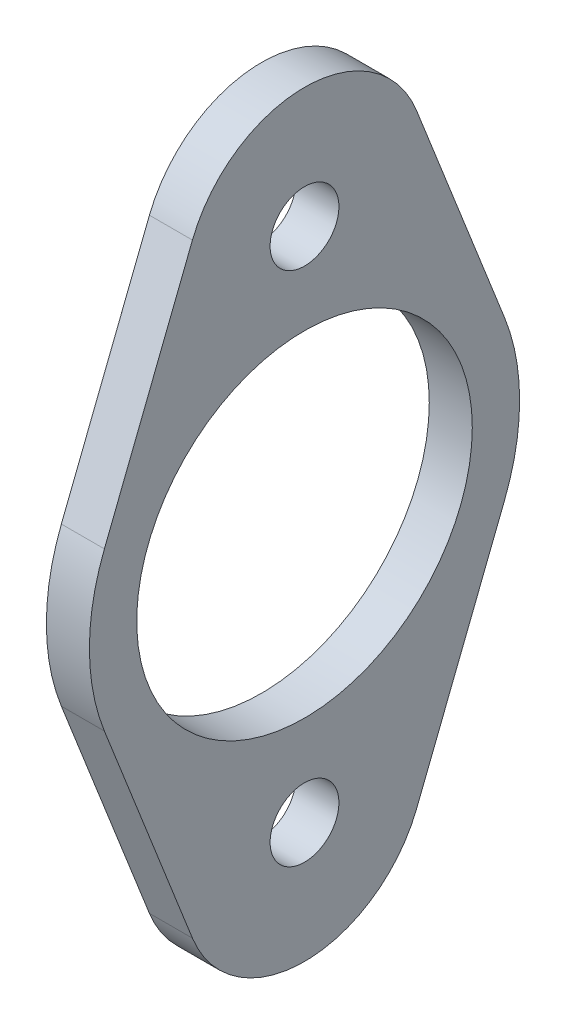
SolidWorks part; units mm, degrees
ref_plane "Front Plane" through (0, 0, 0) normal (1, 0, 0) x (0, 1, 0)
ref_plane "Top Plane" through (0, 0, 0) normal (0, 0, 1) x (0, 1, 0)
ref_plane "Right Plane" through (0, 0, 0) normal (0, 1, 0) x (-1, 0, 0)
sketch "Sketch1" plane through (0, 0, 0) normal (1, 0, 0) x (0, 1, 0)
  line L0 (-30, 0) -> (30, 0) construction
  line L1 (-35.1333, 13.0249) -> (-9.1667, 23.2588)
  line L2 (9.1667, 23.2588) -> (35.1333, 13.0249)
  line L3 (-35.1333, -13.0249) -> (-9.1667, -23.2588)
  line L4 (9.1667, -23.2588) -> (35.1333, -13.0249)
  circle A0 centre (0, 0) radius 19.5
  arc A1 (-9.1667, -23.2588) -> (9.1667, -23.2588) centre (0, 0) ccw
  circle A2 centre (30, 0) radius 4
  circle A3 centre (-30, 0) radius 4
  arc A4 (-35.1333, 13.0249) -> (-35.1333, -13.0249) centre (-30, 0) ccw
  circle A6 centre (-30, 0) radius 14 construction
  arc A7 (9.1667, 23.2588) -> (-9.1667, 23.2588) centre (0, 0) ccw
  arc A9 (35.1333, -13.0249) -> (35.1333, 13.0249) centre (30, 0) ccw
  point P7 (0, 0)
  dimension "D3" = 8
  dimension "D4" = 39
  dimension "D5" = 50
  dimension "D2" = 60
  dimension "D1" = 10
extrude "Boss-Extrude1" add sketch "Sketch1" along normal mid plane 5 contours L1 A7 L2 A9 L4 A1 L3 A4
